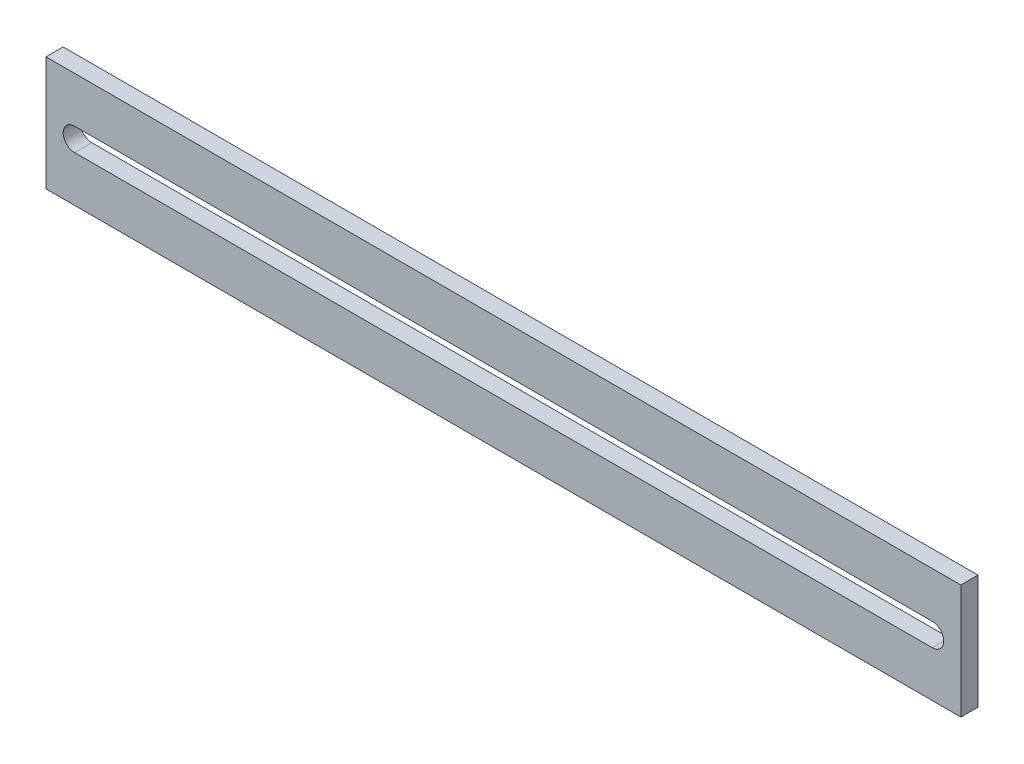
SolidWorks part; units mm, degrees
ref_plane "Front Plane" through (0, 0, 0) normal (0, 0, 1) x (1, 0, 0)
ref_plane "Top Plane" through (0, 0, 0) normal (0, 1, 0) x (1, 0, 0)
ref_plane "Right Plane" through (0, 0, 0) normal (1, 0, 0) x (0, 0, -1)
sketch "Sketch1" plane through (0, 0, 0) normal (0, 0, 1) x (1, 0, 0)
  line L1 (-80, 10) -> (80, 10)
  line L2 (-80, 10) -> (-80, -10)
  line L3 (-80, -10) -> (80, -10)
  line L4 (80, 10) -> (80, -10)
  line L5 (-80, 10) -> (80, -10) construction
  line L6 (-80, -10) -> (80, 10) construction
  point P0 (0, 0)
  dimension "D1" = 20
  dimension "D2" = 160
extrude "Boss-Extrude1" add sketch "Sketch1" along normal blind 3
sketch "Sketch2" plane through (0, 0, 3) normal (0, 0, 1) x (1, 0, 0)
  line L0 (-75, 0) -> (75, 0) construction
  line L1 (-75, 2) -> (75, 2)
  line L2 (-75, -2) -> (75, -2)
  line L5 (-80, 10) -> (-80, -10) construction
  line L6 (80, -10) -> (80, 10) construction
  arc A0 (-75, 2) -> (-75, -2) centre (-75, 0) ccw
  arc A1 (75, -2) -> (75, 2) centre (75, 0) ccw
  point P3 (0, 0)
  dimension "D1" = 2
  dimension "D2" = 5
  dimension "D3" = 5
extrude "Cut-Extrude1" cut sketch "Sketch2" against normal blind 3
